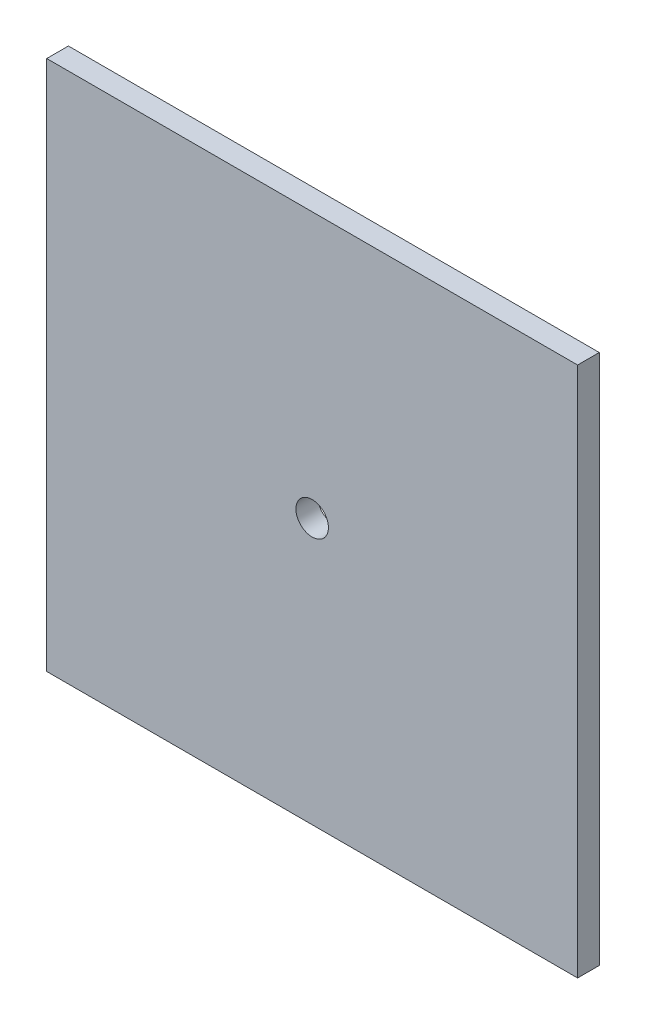
SolidWorks part; units mm, degrees
ref_plane "Plan de face" through (0, 0, 0) normal (0, 0, 1) x (1, 0, 0)
ref_plane "Plan de dessus" through (0, 0, 0) normal (0, 1, 0) x (1, 0, 0)
ref_plane "Plan de droite" through (0, 0, 0) normal (1, 0, 0) x (0, 0, -1)
sketch "Esquisse1" plane through (0, 0, 0) normal (0, 0, 1) x (1, 0, 0)
  line L1 (-24.5, 24.5) -> (24.5, 24.5)
  line L2 (-24.5, 24.5) -> (-24.5, -24.5)
  line L3 (-24.5, -24.5) -> (24.5, -24.5)
  line L4 (24.5, 24.5) -> (24.5, -24.5)
  line L5 (-24.5, 24.5) -> (24.5, -24.5) construction
  line L6 (-24.5, -24.5) -> (24.5, 24.5) construction
  circle A0 centre (0, 0) radius 1.5
  point P0 (0, 0)
  point P27 (0, 0)
extrude "Boss.-Extru.1" add sketch "Esquisse1" along normal blind 2
